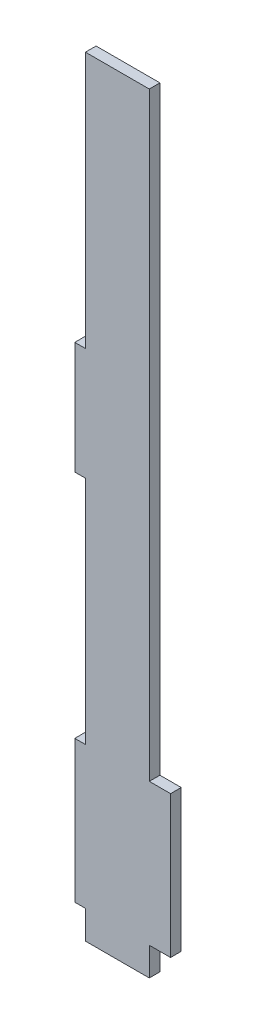
SolidWorks part; units mm, degrees
ref_plane "Front Plane" through (0, 0, 0) normal (0, 0, 1) x (1, 0, 0)
ref_plane "Top Plane" through (0, 0, 0) normal (0, 1, 0) x (1, 0, 0)
ref_plane "Right Plane" through (0, 0, 0) normal (1, 0, 0) x (0, 0, -1)
sketch "Sketch1" plane through (0, 0, 0) normal (0, 0, 1) x (1, 0, 0)
  line L1 (-18, 61) -> (0, 61)
  line L2 (-18, 61) -> (-18, 0)
  line L3 (-18, 0) -> (0, 0)
  line L4 (0, 61) -> (0, 0)
  dimension "D1" = 61
  dimension "D2" = 18
extrude "Base Shape" add sketch "Sketch1" along normal blind 3
sketch "Sketch2" plane through (0, 0, 3) normal (0, 0, 1) x (1, 0, 0)
  line L0 (-18, 61) -> (-18, 0) construction
  line L1 (-18, 8) -> (-21, 8)
  line L2 (-18, 8) -> (-18, 48)
  line L3 (-18, 48) -> (-21, 48)
  line L4 (-21, 8) -> (-21, 48)
  line L5 (0, 0) -> (0, 61) construction
  line L6 (0, 8) -> (6, 8)
  line L7 (0, 8) -> (0, 48)
  line L8 (0, 48) -> (6, 48)
  line L9 (6, 8) -> (6, 48)
  line L10 (-18, 0) -> (0, 0) construction
  line M11 (0, 0) -> (0, 61)
  dimension "D1" = 8
  dimension "D2" = 40
  dimension "D3" = 3
  dimension "D4" = 6
extrude "Fingers" add sketch "Sketch2" against normal up to surface (3 mm away) contours L6 L9 L8 M11 | L4 L3 L2 L1 up to face at (-9, 30.5, 0)
sketch "Sketch3" plane through (0, 61, 0) normal (0, 1, 0) x (1, 0, 0)
  line L1 (-18, 0) -> (0, 0)
  line L2 (-18, 0) -> (-18, -3)
  line L3 (-18, -3) -> (0, -3)
  line L4 (0, 0) -> (0, -3)
extrude "Boss-Extrude1" add sketch "Sketch3" along normal blind 156
sketch "Sketch4" plane through (0, 0, 3) normal (0, 0, 1) x (1, 0, 0)
  line L0 (-18, 217) -> (-18, 48) construction
  line L1 (-18, 113) -> (-21, 113)
  line L2 (-18, 113) -> (-18, 144.6661)
  line L3 (-18, 144.6661) -> (-21, 144.6661)
  line L4 (-21, 113) -> (-21, 144.6661)
  line L5 (-21, 8) -> (-21, 48) construction
  line L6 (-18, 48) -> (-21, 48) construction
  dimension "D1" = 65
extrude "Boss-Extrude3" add sketch "Sketch4" against normal through all
